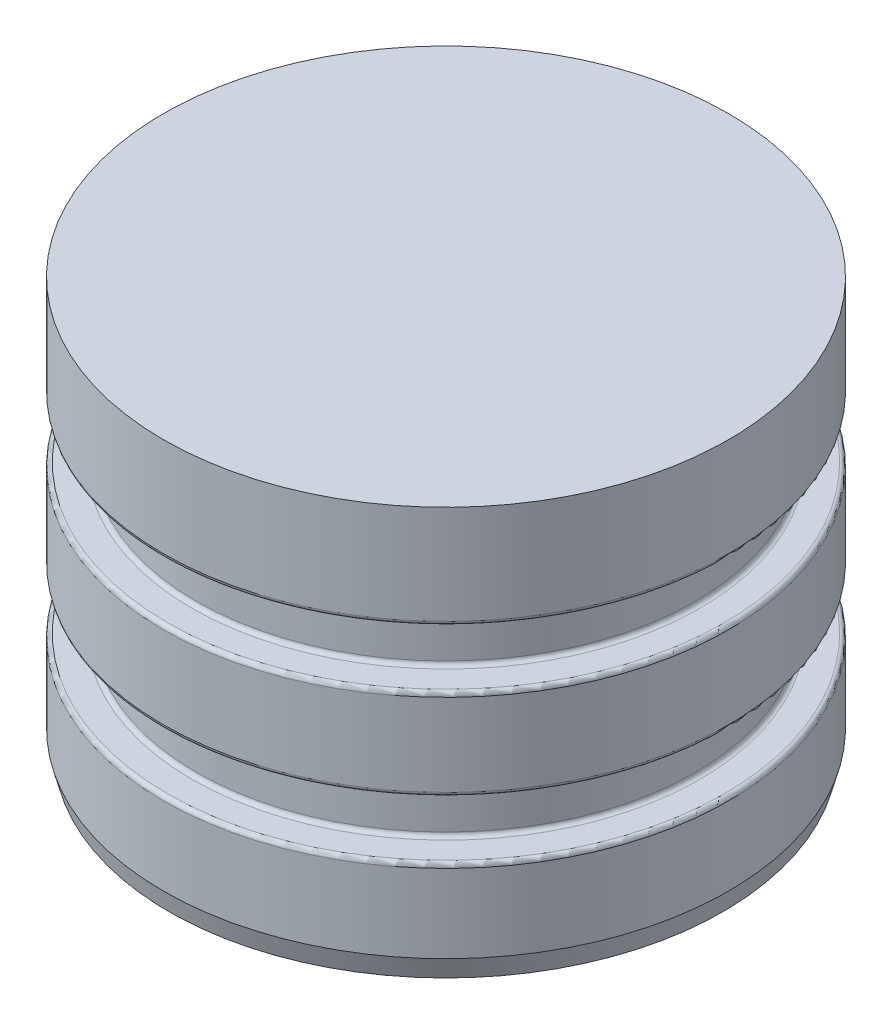
SolidWorks part; units mm, degrees
ref_plane "Front Plane" through (0, 0, 0) normal (0, 0, 1) x (1, 0, 0)
ref_plane "Top Plane" through (0, 0, 0) normal (0, 1, 0) x (1, 0, 0)
ref_plane "Right Plane" through (0, 0, 0) normal (1, 0, 0) x (0, 0, -1)
sketch "Sketch2" plane through (0, 0, 0) normal (0, 0, 1) x (1, 0, 0)
  line L0 (0, 0) -> (0, -38191.5326) construction
  line L1 (0, 25.4) -> (-17.4371, 25.4)
  line L2 (-17.4371, 25.4) -> (-17.4371, 19.05)
  line L3 (-17.4371, 19.05) -> (-15.4051, 19.05)
  line L4 (-15.4051, 19.05) -> (-15.4051, 15.494)
  line L5 (-15.4051, 15.494) -> (-17.4371, 15.494)
  line L6 (-17.4371, 15.494) -> (-17.4371, 9.906)
  line L7 (-17.4371, 9.906) -> (-15.4051, 9.906)
  line L8 (-15.4051, 9.906) -> (-15.4051, 6.35)
  line L9 (-15.4051, 6.35) -> (-17.4371, 6.35)
  line L10 (-17.4371, 6.35) -> (-17.4371, 0)
  line L11 (-17.4371, 0) -> (0, 0)
  line L12 (0, 25.4) -> (0, 0)
  dimension "D1" = 25.4
  dimension "D2" = 6.35
  dimension "D3" = 3.556
  dimension "D4" = 3.556
  dimension "D5" = 6.35
  dimension "D6" = 34.8742
  dimension "D7" = 30.8102
revolve "Revolve1" add sketch "Sketch2" angle 360 about L0
sketch "Sketch3" plane through (0, 0, 0) normal (0, -1, 0) x (1, 0, 0)
  circle A0 centre (0, 0) radius 8.763
  dimension "D1" = 17.526
extrude "Cut-Extrude1" cut sketch "Sketch3" against normal offset from surface (22.098 mm away) 3.302 up to face at (0, 25.4, 17.4371)
fillet "Fillet3" radius 0.254 8 edges at (0, 6.35, 15.4051) (0, 9.906, 15.4051) (0, 15.494, 15.4051) (0, 19.05, 15.4051) (0, 6.35, 17.4371) (0, 9.906, 17.4371) (0, 15.494, 17.4371) (0, 19.05, 17.4371)
chamfer "Chamfer1" distance 1.27 angle 15 1 edges at (0, 0, 17.4371)
